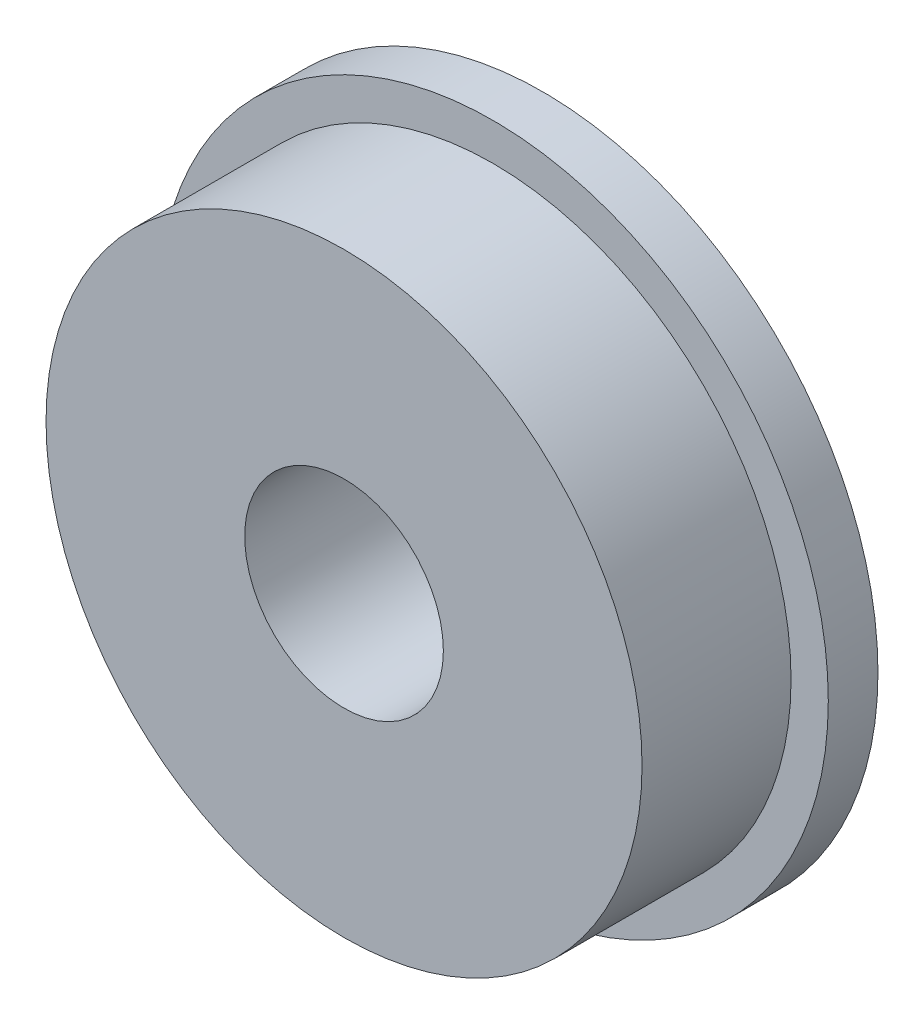
SolidWorks part; units mm, degrees
ref_plane "Front Plane" through (0, 0, 0) normal (0, 0, 1) x (1, 0, 0)
ref_plane "Top Plane" through (0, 0, 0) normal (0, 1, 0) x (1, 0, 0)
ref_plane "Right Plane" through (0, 0, 0) normal (1, 0, 0) x (0, 0, -1)
sketch "Sketch1" plane through (0, 0, 0) normal (0, 0, 1) x (1, 0, 0)
  circle A0 centre (0, 0) radius 6.75
  circle A1 centre (0, 0) radius 2
  dimension "D1" = 13.5
  dimension "D2" = 4
extrude "Boss-Extrude1" add sketch "Sketch1" along normal blind 4
sketch "Sketch2" plane through (0, 0, 4) normal (0, 0, 1) x (1, 0, 0)
  circle A0 centre (0, 0) radius 6
  circle A1 centre (0, 0) radius 6.75
  dimension "D1" = 12
extrude "Cut-Extrude1" cut sketch "Sketch2" against normal blind 3
